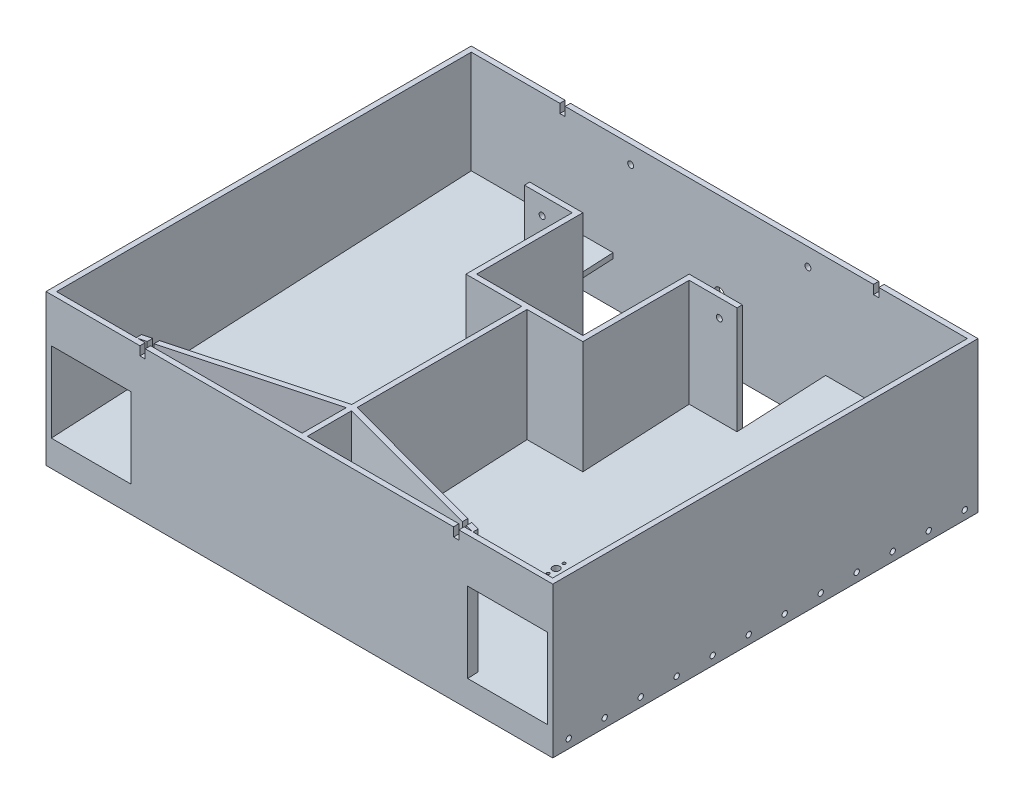
SolidWorks part; units mm, degrees
ref_plane "前视基准面" through (0, 0, 0) normal (0, 0, 1) x (1, 0, 0)
ref_plane "上视基准面" through (0, 0, 0) normal (0, 1, 0) x (1, 0, 0)
ref_plane "右视基准面" through (0, 0, 0) normal (1, 0, 0) x (0, 0, -1)
sketch "草图1" plane through (0, 0, 0) normal (0, 1, 0) x (1, 0, 0)
  line L1 (-143, 120) -> (143, 120)
  line L2 (-143, 120) -> (-143, -120)
  line L3 (-143, -120) -> (143, -120)
  line L4 (143, 120) -> (143, -120)
  line L5 (-143, 120) -> (143, -120) construction
  line L6 (-143, -120) -> (143, 120) construction
  line L7 (-140, 117) -> (140, 117)
  line L8 (-140, 117) -> (-140, -117)
  line L9 (-140, -117) -> (140, -117)
  line L10 (140, 117) -> (140, -117)
  line L11 (-140, 117) -> (140, -117) construction
  line L12 (-140, -117) -> (140, 117) construction
  point P0 (0, 0)
  point P6 (0, 0)
  dimension "D1" = 286
  dimension "D2" = 240
  dimension "D3" = 3
  dimension "D4" = 3
extrude "凸台-拉伸1" add sketch "草图1" along normal blind 85
sketch "草图2" plane through (-140, 0, 0) normal (1, 0, 0) x (0, 0, -1)
  line L0 (117, 27) -> (-117, 15)
  line L1 (117, 85) -> (117, 0) construction
  line L2 (-117, 85) -> (-117, 0) construction
  line L3 (-117, 15) -> (-117, 11.9961)
  line L4 (-117, 11.9961) -> (117, 23.9961)
  line L5 (117, 23.9961) -> (117, 27)
  line L6 (117, 0) -> (-117, 0) construction
  dimension "D1" = 15
  dimension "D2" = 3
  dimension "D3" = 27
extrude "凸台-拉伸2" add sketch "草图2" along normal up to surface (280 mm away) up to face at (140, 42.5, 0)
sketch "草图3" plane through (0, 85, 0) normal (0, 1, 0) x (1, 0, 0)
  line L0 (-143, -120) -> (143, -120) construction
  line L1 (-140, -117) -> (-95, -117)
  line L2 (-140, -117) -> (-140, -120)
  line L3 (-140, -120) -> (-95, -120)
  line L4 (-95, -117) -> (-95, -120)
  line L6 (140, -117) -> (95, -117)
  line L7 (140, -117) -> (140, -120)
  line L8 (140, -120) -> (95, -120)
  line L9 (95, -117) -> (95, -120)
  dimension "D1" = 45
  dimension "D2" = 45
extrude "切除-拉伸1" cut sketch "草图3" against normal up to surface (70 mm away)
sketch "草图5" plane through (0, 85, 0) normal (0, 1, 0) x (1, 0, 0)
  line L0 (-60, 117) -> (-60, 70)
  line L1 (140, 117) -> (-140, 117) construction
  line L2 (-60, 70) -> (-30, 70)
  line L3 (-30, 70) -> (-30, 10)
  line L4 (-30, 10) -> (30, 10)
  line L5 (30, 10) -> (30, 70)
  line L6 (30, 70) -> (60, 70)
  line L7 (60, 70) -> (60, 117)
  line L8 (140, 117) -> (-140, 117) construction
  line L9 (60, 117) -> (-60, 117)
  line L10 (0, 10) -> (0, 120) construction
  line L11 (143, 120) -> (-143, 120) construction
  dimension "D1" = 120
  dimension "D2" = 47
  dimension "D3" = 60
  dimension "D4" = 60
extrude "切除-拉伸2" cut sketch "草图5" against normal through all
sketch "草图6" plane through (0, 85, 0) normal (0, 1, 0) x (1, 0, 0)
  line L2 (-33, 67) -> (-33, 7)
  line L3 (-33, 7) -> (-1.5, 7)
  line L4 (-1.5, 7) -> (-1.5, -88.8929)
  line L5 (95, -117) -> (-95, -117) construction
  line L14 (-30, 10) -> (-30, 70)
  line L15 (0, 10) -> (0, -120) construction
  line L16 (30, 10) -> (-30, 10) construction
  line L17 (-95, -120) -> (95, -120) construction
  line L18 (-1.5, -117) -> (1.5, -117)
  line L19 (30, 10) -> (30, 70)
  line L20 (1.5, 7) -> (1.5, -88.8929)
  line L21 (33, 7) -> (1.5, 7)
  line L22 (33, 67) -> (33, 7)
  line L24 (-30, 10) -> (30, 10)
  line L25 (-94.219, -117) -> (-1.5, -92)
  line L26 (-95, -114.1034) -> (-1.5, -88.8929)
  line L27 (-60, 70) -> (-60, 67)
  line L28 (-1.5, -92) -> (-1.5, -117)
  line L29 (-95, -114.1034) -> (-95, -117)
  line L30 (-94.219, -117) -> (-95, -117)
  line L31 (-95, -117) -> (95, -117) construction
  line L32 (1.5, -88.8929) -> (95, -114.1034)
  line L33 (95, -114.1034) -> (95, -117)
  line L34 (95, -117) -> (94.219, -117)
  line L35 (94.219, -117) -> (1.5, -92)
  line L36 (-95, -114.1034) -> (-94.219, -117) construction
  line L37 (1.5, -92) -> (1.5, -117)
  line L38 (-60, 67) -> (-33, 67)
  line L40 (33, 67) -> (60, 67)
  line L41 (60, 67) -> (60, 70)
  line L42 (60, 70) -> (30, 70)
  line L43 (60, 70) -> (30, 70) construction
  line L44 (-60, 70) -> (-30, 70)
  point P22 (0, -117)
  dimension "D1" = 3
  dimension "D2" = 1.5
  dimension "D3" = 3
  dimension "D4" = 3
  dimension "D5" = 25
  dimension "D6" = 3
extrude "凸台-拉伸3" add sketch "草图6" against normal up to surface (60.4103 mm away)
sketch "草图7" plane through (0, 85, 0) normal (0, 1, 0) x (1, 0, 0)
  line L0 (-95, -120) -> (-95, -114.1034) construction
  line L1 (-95, -117.0517) -> (-140, -117.0517)
  line L2 (-95, -117.0517) -> (-95, -120)
  line L3 (-95, -120) -> (-140, -120)
  line L4 (-140, -117.0517) -> (-140, -120)
  line L5 (95, -117.0517) -> (140, -117.0517)
  line L6 (95, -117.0517) -> (95, -120)
  line L7 (95, -120) -> (140, -120)
  line L8 (140, -117.0517) -> (140, -120)
  line L9 (95, -114.1034) -> (95, -120) construction
extrude "凸台-拉伸4" add sketch "草图7" against normal blind 25
sketch "草图8" plane through (0, 0, -70) normal (0, 0, -1) x (-1, 0, 0)
  line L5 (60, 24.5897) -> (60, 85) construction
  line L10 (-60, 21.5858) -> (60, 21.5858)
  line L11 (-60, 21.5858) -> (-60, 9.5858)
  line L12 (-60, 9.5858) -> (60, 9.5858)
  line L13 (60, 21.5858) -> (60, 9.5858)
  dimension "D2" = 12
extrude "凸台-拉伸5" add sketch "草图8" against normal up to surface (3 mm away) up to face at (-46.5, 54.7179, -67)
sketch "草图9" plane through (0, 0, -120) normal (0, 0, -1) x (-1, 0, 0)
  line L0 (0, 85) -> (0, 0) construction
  line L1 (-143, 85) -> (143, 85) construction
  line L2 (-50, 75) -> (50, 75) construction
  circle A0 centre (-50, 75) radius 1.7
  circle A1 centre (50, 75) radius 1.7
  circle A2 centre (0, 37) radius 3
  point P11 (0, 75)
  dimension "D1" = 3.4
  dimension "D2" = 6
  dimension "D3" = 48
  dimension "D4" = 100
  dimension "D5" = 10
extrude "切除-拉伸3" cut sketch "草图9" against normal up to surface (53 mm away) up to face at (-46.5, 54.7179, -67)
sketch "草图10" plane through (0, 0, -70) normal (0, 0, -1) x (-1, 0, 0)
  line L0 (-50, 75) -> (-50, 16) construction
  line L1 (-50, 16) -> (50, 16) construction
  line L2 (50, 75) -> (50, 16) construction
  circle A0 centre (-50, 16) radius 1.7
  circle A1 centre (50, 16) radius 1.7
  circle A2 centre (-50, 75) radius 1.7 construction
  dimension "D1" = 59
extrude "切除-拉伸4" cut sketch "草图10" against normal up to next
sketch "草图11" plane through (-143, 0, 0) normal (-1, 0, 0) x (0, 0, 1)
  line L0 (-120, 0) -> (120, 0) construction
  line L2 (120, 85) -> (120, 0) construction
  circle A0 centre (111, 5) radius 1.5
  dimension "D1" = 3
  dimension "D2" = 5
  dimension "D3" = 9
extrude "切除-拉伸5" cut sketch "草图11" against normal through all
pattern_linear "阵列(线性)1" count 12 spacing 20.32 along (0, 0, -1) of "切除-拉伸5"
sketch "草图12" plane through (0, 17.9489, 0.9205) normal (0, -0.9987, -0.0512) x (1, 0, 0)
  line L0 (-30, -68.0097) -> (-30, -10.9348)
  line L1 (-30, -10.9348) -> (30, -10.9348)
  line L2 (30, -10.9348) -> (30, -68.0097)
  line L3 (30, -68.0097) -> (33, -68.0097)
  line L4 (30, -68.0097) -> (60, -68.0097) construction
  line L5 (33, -68.0097) -> (33, -7.9348)
  line L6 (33, -7.9348) -> (1.5, -7.9348)
  line L7 (1.5, -7.9348) -> (1.5, 22.0652)
  line L8 (1.5, 22.0652) -> (-1.5, 22.0652)
  line L9 (-1.5, 22.0652) -> (-1.5, -7.9348)
  line L10 (-1.5, -7.9348) -> (-33, -7.9348)
  line L11 (-33, -7.9348) -> (-33, -68.0097)
  line L12 (-60, -68.0097) -> (-30, -68.0097) construction
  line L13 (-33, -68.0097) -> (-30, -68.0097)
  line L14 (0, 22.0652) -> (0, -10.9348) construction
  line L15 (-64.2541, 107.9843) -> (-25.6368, 97.5582)
  line L16 (-25.6368, 97.5582) -> (-26.4187, 94.6619)
  line L17 (-26.4187, 94.6619) -> (-65.036, 105.088)
  line L18 (-65.036, 105.088) -> (-64.2541, 107.9843)
  line L19 (25.6368, 97.5582) -> (64.2541, 107.9843)
  line L20 (64.2541, 107.9843) -> (65.036, 105.088)
  line L21 (65.036, 105.088) -> (26.4187, 94.6619)
  line L22 (26.4187, 94.6619) -> (25.6368, 97.5582)
  dimension "D1" = 3
  dimension "D2" = 3
  dimension "D3" = 3
  dimension "D4" = 3
  dimension "D5" = 30
  dimension "D6" = 25
  dimension "D7" = 40
  dimension "D8" = 3
extrude "凸台-拉伸6" add sketch "草图12" along normal up to surface (8.781 mm away)
sketch "草图17" plane through (0, -35, -120) normal (0, 0, 1) x (1, 0, 0)
  line L6 (143, 120) -> (-143, 120) construction
  line L11 (90, 120) -> (87, 120)
  line L12 (90, 120) -> (90, 115)
  line L13 (90, 115) -> (87, 115)
  line L14 (87, 120) -> (87, 115)
  line L15 (87, 117.5) -> (-87, 117.5) construction
  line L16 (-87, 120) -> (-90, 120)
  line L17 (-87, 120) -> (-87, 115)
  line L18 (-87, 115) -> (-90, 115)
  line L19 (-90, 120) -> (-90, 115)
  line L20 (0, 120) -> (0, 35) construction
  line L21 (143, 35) -> (-143, 35) construction
  point P16 (0, 117.5)
  dimension "D1" = 3
  dimension "D2" = 5
  dimension "D3" = 174
extrude "切除-拉伸7" cut sketch "草图17" along normal up to surface (240 mm away) up to face at (0, 42.5, 120)
sketch "草图18" plane through (0, 20.9449, 1.0741) normal (0, 0.9987, 0.0512) x (1, 0, 0)
  line L0 (-70, -39.5822) -> (-70, -48.5822) construction
  line L1 (-140, 121.1997) -> (-140, -112.5449) construction
  line L2 (-140, -119.0822) -> (-95, -119.0822) construction
  line L3 (0, -115.4893) -> (0, 0) construction
  line L4 (-87, -115.4893) -> (87, -115.4893) construction
  line L5 (70, -39.5822) -> (70, -48.5822) construction
  circle A0 centre (-70, -44.0822) radius 2
  circle A1 centre (-70, -39.5822) radius 0.8
  circle A2 centre (-70, -48.5822) radius 0.8
  circle A3 centre (70, -48.5822) radius 0.8
  circle A4 centre (70, -39.5822) radius 0.8
  circle A5 centre (70, -44.0822) radius 2
  dimension "D1" = 4
  dimension "D2" = 1.6
  dimension "D3" = 9
  dimension "D4" = 70
  dimension "D5" = 75
extrude "切除-拉伸8" cut sketch "草图18" against normal up to next
